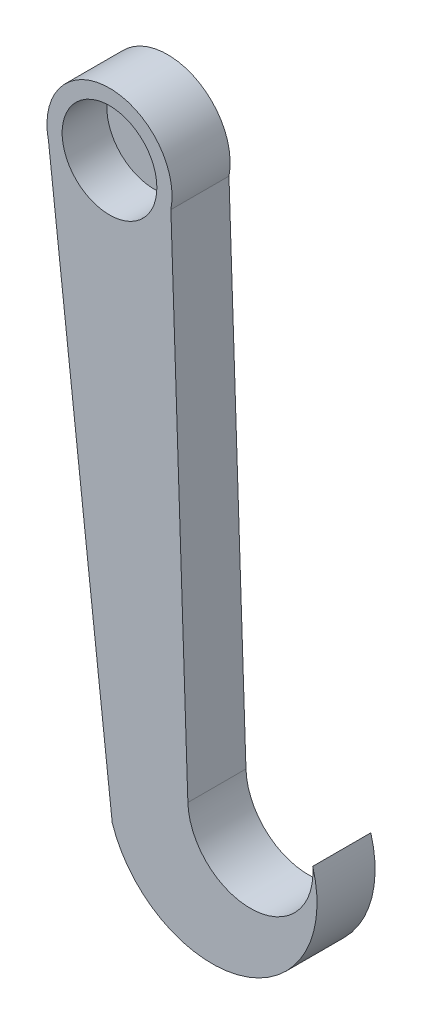
SolidWorks part; units mm, degrees
ref_plane "정면" through (0, 0, 0) normal (0, 0, 1) x (1, 0, 0)
ref_plane "윗면" through (0, 0, 0) normal (0, 1, 0) x (1, 0, 0)
ref_plane "우측면" through (0, 0, 0) normal (1, 0, 0) x (0, 0, -1)
sketch "스케치1" plane through (0, 0, 0) normal (0, 0, 1) x (1, 0, 0)
  circle A0 centre (0, 0) radius 14
  dimension "D1" = 28
extrude "보스-돌출1" add sketch "스케치1" along normal blind 13
sketch "스케치2" plane through (0, 0, 0) normal (0, 0, -1) x (-1, 0, 0)
  circle A0 centre (0, 0) radius 10.6
  dimension "D1" = 21.2
sketch "스케치3" plane through (0, 0, 13) normal (0, 0, 1) x (1, 0, 0)
  circle A0 centre (0, 0) radius 4
  dimension "D1" = 8
extrude "컷-돌출2" cut sketch "스케치3" against normal blind 10
sketch "스케치6" plane through (0, 0, 13) normal (0, 0, 1) x (1, 0, 0)
  line L0 (0, 0) -> (0, 18.4707) construction
  line L1 (-14, 37.9731) -> (-14, -35.8302) construction
  line L2 (14, 37.9731) -> (14, -35.8302) construction
  line L3 (13.7356, -2.7081) -> (17.5397, -115.7081)
  line L4 (-13.649, -3.1153) -> (0.6086, -128.1153)
  arc A0 (17.5397, -115.7081) -> (45.486, -114.1067) centre (31.5317, -115.2371) ccw
  circle A1 centre (0, 0) radius 14 construction
  arc A2 (0.6086, -128.1153) -> (45.486, -114.1067) centre (22.9334, -120.746) ccw
  arc A3 (-13.649, -3.1153) -> (13.7356, -2.7081) centre (0, 0) ccw
  dimension "D3" = 14
  dimension "D1" = 113
  dimension "D2" = 125
extrude "보스-돌출3" add sketch "스케치6" against normal blind 13
sketch "스케치7" plane through (0, 0, 13) normal (0, 0, 1) x (1, 0, 0)
  circle A0 centre (0, 0) radius 10.6
extrude "컷-돌출3" cut sketch "스케치7" against normal blind 10
